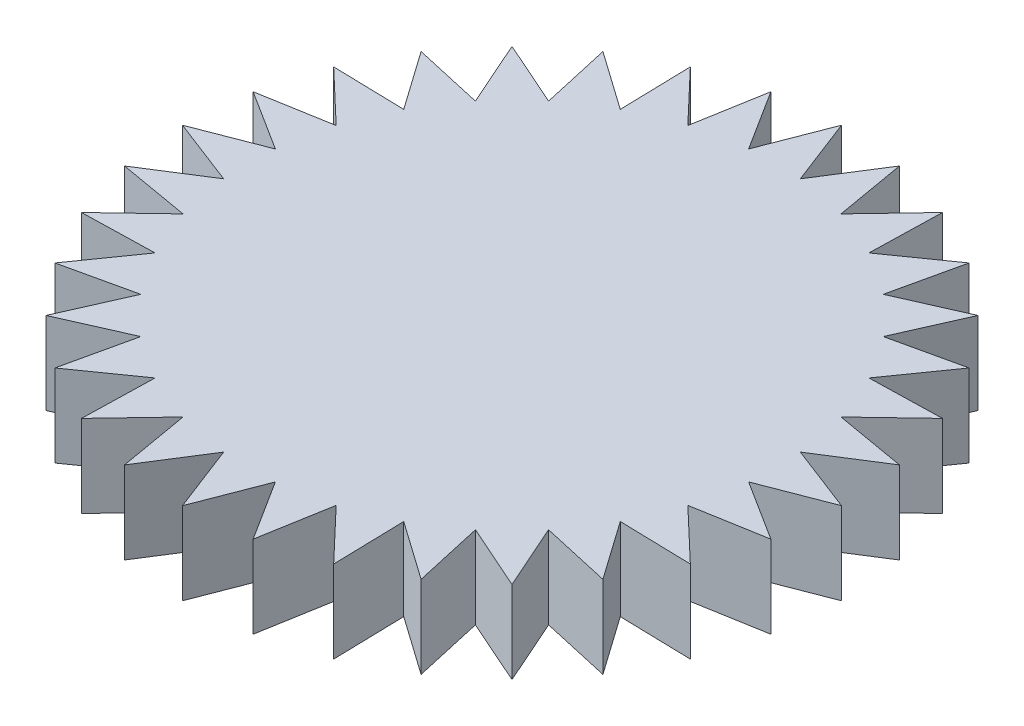
SolidWorks part; units mm, degrees
ref_plane "Plan de face" through (0, 0, 0) normal (0, 0, 1) x (1, 0, 0)
ref_plane "Plan de dessus" through (0, 0, 0) normal (0, 1, 0) x (1, 0, 0)
ref_plane "Plan de droite" through (0, 0, 0) normal (1, 0, 0) x (0, 0, -1)
sketch "Esquisse1" plane through (0, 0, 0) normal (0, 1, 0) x (1, 0, 0)
  circle A0 centre (0, 0) radius 20
  dimension "D1" = 40
extrude "Boss.-Extru.1" add sketch "Esquisse1" along normal blind 5
sketch "Esquisse2" plane through (0, 5, 0) normal (0, 1, 0) x (1, 0, 0)
  line L0 (0, 20) -> (0, 12.1116) construction
  line L1 (0, 20) -> (1.9789, 14.8689)
  line L2 (0, 20) -> (-1.9789, 14.8689)
  line L3 (3.9018, 19.6157) -> (0.9599, 14.9693)
  line L4 (3.9018, 19.6157) -> (4.8417, 14.1971)
  line L5 (7.6537, 18.4776) -> (3.8618, 14.4944)
  line L6 (7.6537, 18.4776) -> (7.5184, 12.9798)
  line L7 (11.1114, 16.6294) -> (6.6153, 13.4625)
  line L8 (11.1114, 16.6294) -> (9.9061, 11.2636)
  line L9 (14.1421, 14.1421) -> (9.1146, 11.9132)
  line L10 (14.1421, 14.1421) -> (11.9132, 9.1146)
  line L11 (16.6294, 11.1114) -> (11.2636, 9.9061)
  line L12 (16.6294, 11.1114) -> (13.4625, 6.6153)
  line L13 (18.4776, 7.6537) -> (12.9798, 7.5184)
  line L14 (18.4776, 7.6537) -> (14.4944, 3.8618)
  line L15 (19.6157, 3.9018) -> (14.1971, 4.8417)
  line L16 (19.6157, 3.9018) -> (14.9693, 0.9599)
  line L17 (20, 0) -> (14.8689, 1.9789)
  line L18 (20, 0) -> (14.8689, -1.9789)
  line L19 (19.6157, -3.9018) -> (14.9693, -0.9599)
  line L20 (19.6157, -3.9018) -> (14.1971, -4.8417)
  line L21 (18.4776, -7.6537) -> (14.4944, -3.8618)
  line L22 (18.4776, -7.6537) -> (12.9798, -7.5184)
  line L23 (16.6294, -11.1114) -> (13.4625, -6.6153)
  line L24 (16.6294, -11.1114) -> (11.2636, -9.9061)
  line L25 (14.1421, -14.1421) -> (11.9132, -9.1146)
  line L26 (14.1421, -14.1421) -> (9.1146, -11.9132)
  line L27 (11.1114, -16.6294) -> (9.9061, -11.2636)
  line L28 (11.1114, -16.6294) -> (6.6153, -13.4625)
  line L29 (7.6537, -18.4776) -> (7.5184, -12.9798)
  line L30 (7.6537, -18.4776) -> (3.8618, -14.4944)
  line L31 (3.9018, -19.6157) -> (4.8417, -14.1971)
  line L32 (3.9018, -19.6157) -> (0.9599, -14.9693)
  line L33 (0, -20) -> (1.9789, -14.8689)
  line L34 (0, -20) -> (-1.9789, -14.8689)
  line L35 (-3.9018, -19.6157) -> (-0.9599, -14.9693)
  line L36 (-3.9018, -19.6157) -> (-4.8417, -14.1971)
  line L37 (-7.6537, -18.4776) -> (-3.8618, -14.4944)
  line L38 (-7.6537, -18.4776) -> (-7.5184, -12.9798)
  line L39 (-11.1114, -16.6294) -> (-6.6153, -13.4625)
  line L40 (-11.1114, -16.6294) -> (-9.9061, -11.2636)
  line L41 (-14.1421, -14.1421) -> (-9.1146, -11.9132)
  line L42 (-14.1421, -14.1421) -> (-11.9132, -9.1146)
  line L43 (-16.6294, -11.1114) -> (-11.2636, -9.9061)
  line L44 (-16.6294, -11.1114) -> (-13.4625, -6.6153)
  line L45 (-18.4776, -7.6537) -> (-12.9798, -7.5184)
  line L46 (-18.4776, -7.6537) -> (-14.4944, -3.8618)
  line L47 (-19.6157, -3.9018) -> (-14.1971, -4.8417)
  line L48 (-19.6157, -3.9018) -> (-14.9693, -0.9599)
  line L49 (-20, 0) -> (-14.8689, -1.9789)
  line L50 (-20, 0) -> (-14.8689, 1.9789)
  line L51 (-19.6157, 3.9018) -> (-14.9693, 0.9599)
  line L52 (-19.6157, 3.9018) -> (-14.1971, 4.8417)
  line L53 (-18.4776, 7.6537) -> (-14.4944, 3.8618)
  line L54 (-18.4776, 7.6537) -> (-12.9798, 7.5184)
  line L55 (-16.6294, 11.1114) -> (-13.4625, 6.6153)
  line L56 (-16.6294, 11.1114) -> (-11.2636, 9.9061)
  line L57 (-14.1421, 14.1421) -> (-11.9132, 9.1146)
  line L58 (-14.1421, 14.1421) -> (-9.1146, 11.9132)
  line L59 (-11.1114, 16.6294) -> (-9.9061, 11.2636)
  line L60 (-11.1114, 16.6294) -> (-6.6153, 13.4625)
  line L61 (-7.6537, 18.4776) -> (-7.5184, 12.9798)
  line L62 (-7.6537, 18.4776) -> (-3.8618, 14.4944)
  line L63 (-3.9018, 19.6157) -> (-4.8417, 14.1971)
  line L64 (-3.9018, 19.6157) -> (-0.9599, 14.9693)
  circle A0 centre (0, 0) radius 15
  circle A1 centre (0, 0) radius 20
  point P104 (0, 0)
  circle M2 centre (0, 0) radius 20
  dimension "D1" = 30
  dimension "D2" = 40
  dimension "D3" = 32
extrude "Enlèv. mat.-Extru.1" cut sketch "Esquisse2" against normal blind 5 contours L63 L62 M2 | L64 L2 M2 | L3 L1 M2 | L5 L4 M2 | L7 L6 M2 | L9 L8 M2 | L11 L10 M2 | L13 L12 M2 | L15 L14 M2 | L17 L16 M2 | L19 L18 M2 | L21 L20 M2 | L61 L60 M2 | L59 L58 M2 | L57 L56 M2 | L55 L54 M2 | L53 L52 M2 | L51 L50 M2 | L49 L48 M2 | L47 L46 M2 | L45 L44 M2 | L43 L42 M2 | L41 L40 M2 | L39 L38 M2 | L37 L36 M2 | L35 L34 M2 | L33 L32 M2 | L31 L30 M2 | L29 L28 M2 | L27 L26 M2 | L25 L24 M2 | L23 L22 M2
